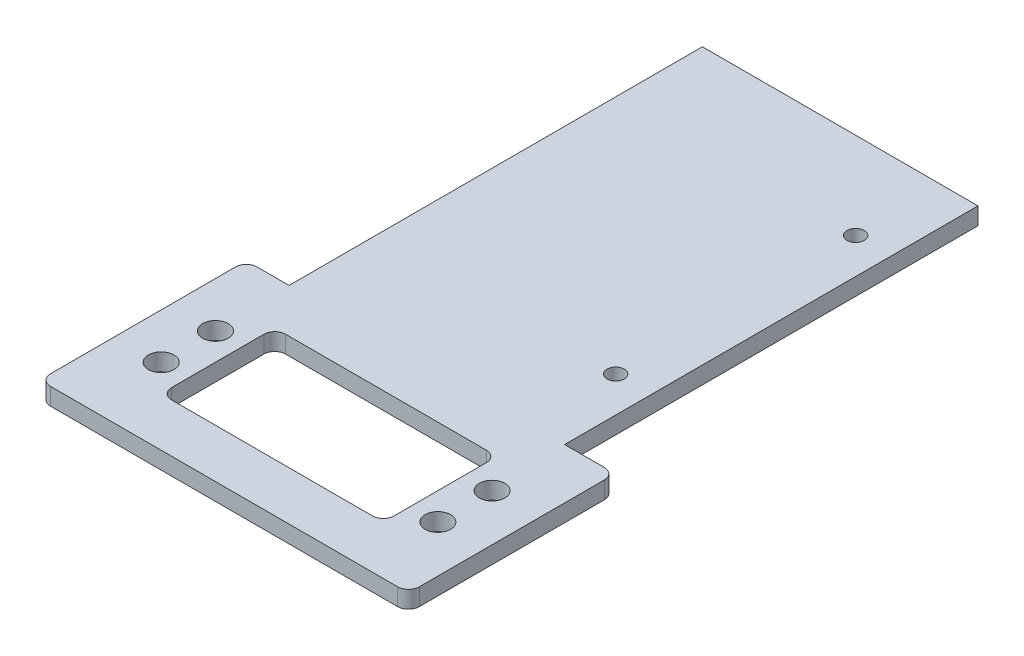
SolidWorks part; units mm, degrees
ref_plane "Front Plane" through (0, 0, 0) normal (0, 0, 1) x (1, 0, 0)
ref_plane "Top Plane" through (0, 0, 0) normal (0, 1, 0) x (1, 0, 0)
ref_plane "Right Plane" through (0, 0, 0) normal (1, 0, 0) x (0, 0, -1)
sketch "Sketch1" plane through (0, 0, 0) normal (0, 1, 0) x (1, 0, 0)
  line L0 (-26.1154, 19.05) -> (-34, 19.05)
  line L1 (34, -19.05) -> (-34, -19.05)
  line L2 (34, -19.05) -> (34, 19.05)
  line L3 (34, 19.05) -> (24.6846, 19.05)
  line L4 (-34, -19.05) -> (-34, 19.05)
  line L5 (34, -19.05) -> (-34, 19.05) construction
  line L6 (34, 19.05) -> (-34, -19.05) construction
  line L8 (-26.1154, 19.05) -> (-26.1154, 95.25)
  line L9 (-26.1154, 95.25) -> (24.6846, 95.25)
  line L10 (24.6846, 19.05) -> (24.6846, 95.25)
  point P0 (0, 0)
  dimension "D1" = 68
  dimension "D2" = 38.1
  dimension "D4" = 50.8
  dimension "D5" = 76.2
extrude "Boss-Extrude1" add sketch "Sketch1" along normal blind 3.175
sketch "Sketch2" plane through (0, 3.175, 0) normal (0, 1, 0) x (1, 0, 0)
  line L0 (-0.1404, -10.0597) -> (-0.1404, 10.9403) construction
  line L3 (-25.6404, 15.1128) -> (24.8596, 15.1128) construction
  line L4 (20.3596, -10.0597) -> (-20.6404, -10.0597)
  line L5 (20.3596, -10.0597) -> (20.3596, 10.9403)
  line L6 (20.3596, 10.9403) -> (-20.6404, 10.9403)
  line L7 (-20.6404, -10.0597) -> (-20.6404, 10.9403)
  line L8 (20.3596, -10.0597) -> (-20.6404, 10.9403) construction
  line L9 (20.3596, 10.9403) -> (-20.6404, -10.0597) construction
  line L10 (-34, 0) -> (34, 0) construction
  line L11 (-34, 19.05) -> (-34, -19.05) construction
  line L12 (34, -19.05) -> (34, 19.05) construction
  line L13 (-25.6404, -5) -> (-25.6404, 5) construction
  line L14 (-26.1154, 33.0186) -> (-10.2404, 33.0186) construction
  line L15 (-26.1154, 95.25) -> (-26.1154, 19.05) construction
  line L16 (-20.6404, 8.2878) -> (-10.2404, 8.2878) construction
  line L17 (-10.2404, 33.0186) -> (-10.2404, 8.2878) construction
  line L18 (-26.1154, 19.05) -> (-34, 19.05) construction
  circle A0 centre (-25.6404, 5) radius 2.35
  circle A4 centre (-25.6404, -5) radius 2.35
  circle A5 centre (25.3596, -5) radius 2.35
  circle A6 centre (25.3596, 5) radius 2.35
  point P6 (0, 0)
  point P23 (-25.6404, 0)
  dimension "D4" = 4.7
  dimension "D1" = 41
  dimension "D2" = 50.5
  dimension "D3" = 10
  dimension "D5" = 21
  dimension "D6" = 15.875
  dimension "D7" = 10.4
  dimension "D8" = 5
extrude "Cut-Extrude1" cut sketch "Sketch2" against normal through all
fillet "Fillet1" radius 2 8 edges at (20.3596, 1.5875, -10.9403) (20.3596, 1.5875, 10.0597) (-20.6404, 1.5875, 10.0597) (-20.6404, 1.5875, -10.9403) (34, 1.5875, -19.05) (34, 1.5875, 19.05) (-34, 1.5875, 19.05) (-34, 1.5875, -19.05)
sketch "Sketch5" plane through (0, 3.175, 0) normal (0, 1, 0) x (1, 0, 0)
  line L0 (18.1346, 34.998) -> (18.1346, 79.248) construction
  line L1 (-26.1154, 95.25) -> (-26.1154, 19.05) construction
  line L3 (24.6846, 95.25) -> (-26.1154, 95.25) construction
  circle A0 centre (18.1346, 79.248) radius 1.5875
  circle A1 centre (18.1346, 34.998) radius 1.5875
  point P7 (0, 0)
  point P8 (18.1346, 70.6237)
  point P9 (0, 0)
  point P10 (0, 0)
  point P11 (0, 0)
  point P12 (0, 0)
  dimension "D1" = 44.25
  dimension "D2" = 3.175
  dimension "D3" = 44.25
  dimension "D4" = 16.002
extrude "Cut-Extrude2" cut sketch "Sketch5" against normal through all
